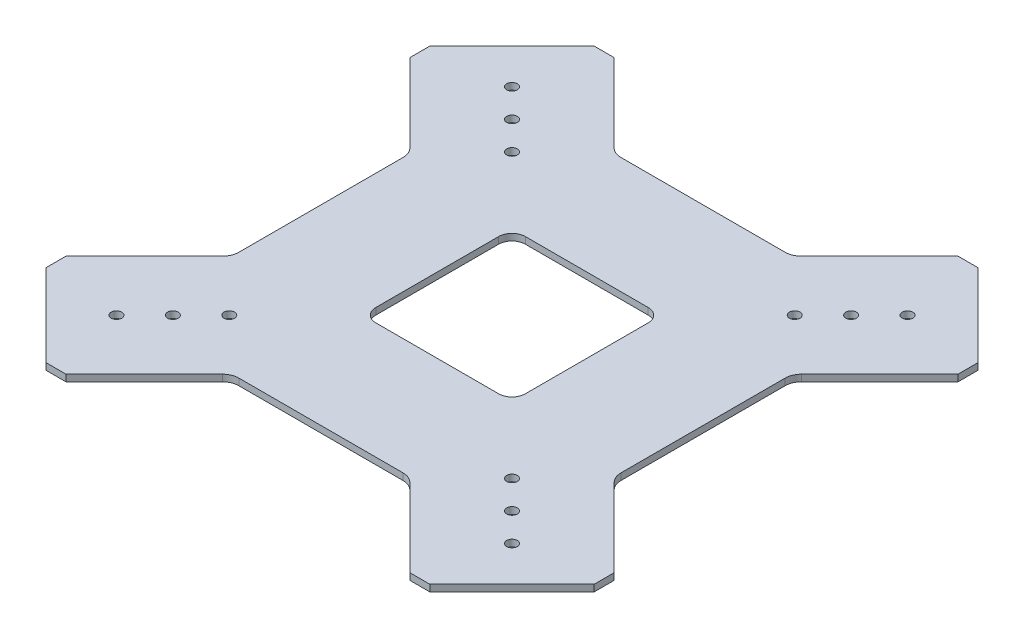
SolidWorks part; units mm, degrees
material "Thornel Mat VMA"
ref_plane "Front Plane" through (0, 0, 0) normal (0, 0, 1) x (1, 0, 0)
ref_plane "Top Plane" through (0, 0, 0) normal (0, 1, 0) x (1, 0, 0)
ref_plane "Right Plane" through (0, 0, 0) normal (1, 0, 0) x (0, 0, -1)
sketch "Sketch1" plane through (0, 0, 0) normal (0, 1, 0) x (1, 0, 0)
  line L0 (-57.7513, 82.5) -> (-82.5, 57.7513)
  line L1 (-57.7513, 82.5) -> (57.7513, 82.5)
  line L2 (-82.5, 57.7513) -> (-82.5, -57.7513)
  line L3 (-57.7513, -82.5) -> (57.7513, -82.5)
  line L4 (82.5, 57.7513) -> (82.5, -57.7513)
  line L5 (-70.1256, 70.1256) -> (70.1256, -70.1256) construction
  line L6 (-70.1256, -70.1256) -> (70.1256, 70.1256) construction
  line L7 (82.5, -57.7513) -> (57.7513, -82.5)
  line L8 (57.7513, 82.5) -> (82.5, 57.7513)
  line L9 (-82.5, -57.7513) -> (-57.7513, -82.5)
  point P0 (0, 0)
  point P9 (-70.1256, 70.1256)
  point P12 (70.1256, -70.1256)
  point P16 (70.1256, 70.1256)
  point P18 (-70.1256, -70.1256)
  dimension "D1" = 165
  dimension "D2" = 35
  dimension "D3" = 35
  dimension "D4" = 35
  dimension "D5" = 35
  dimension "D6" = 165
extrude "Boss-Extrude1" add sketch "Sketch1" along normal blind 2
sketch "Sketch2" plane through (0, 2, 0) normal (0, 1, 0) x (1, 0, 0)
  line L0 (0, -22.5) -> (0, 22.5) construction
  line L5 (22.5, -22.5) -> (-22.5, -22.5)
  line L6 (22.5, -22.5) -> (22.5, 22.5)
  line L7 (22.5, 22.5) -> (-22.5, 22.5)
  line L8 (-22.5, -22.5) -> (-22.5, 22.5)
  line L9 (-22.5, 0) -> (22.5, 0) construction
  dimension "D1" = 45
  dimension "D2" = 45
extrude "Cut-Extrude1" cut sketch "Sketch2" against normal through all
fillet "Fillet1" radius 4 4 edges at (22.5, 1, -22.5) (-22.5, 1, -22.5) (-22.5, 1, 22.5) (22.5, 1, 22.5)
sketch "Sketch3" plane through (0, 2, 0) normal (0, 1, 0) x (1, 0, 0)
  line L0 (51.7513, -82.5) -> (26.7513, -57.5)
  line L1 (-57.7513, -82.5) -> (57.7513, -82.5) construction
  line L2 (26.7513, -57.5) -> (-26.7513, -57.5)
  line L3 (-26.7513, -57.5) -> (-51.7513, -82.5)
  line L4 (0, -82.5) -> (0, -57.5) construction
  line L5 (51.7513, -82.5) -> (-51.7513, -82.5)
  line L6 (51.7513, 82.5) -> (26.7513, 57.5)
  line L7 (57.7513, 82.5) -> (-57.7513, 82.5) construction
  line L8 (26.7513, 57.5) -> (-26.7513, 57.5)
  line L9 (-26.7513, 57.5) -> (-51.7513, 82.5)
  line L10 (-51.7513, 82.5) -> (51.7513, 82.5)
  line L11 (0, 82.5) -> (0, 57.5) construction
  line L12 (82.5, -51.7513) -> (82.5, 51.7513)
  line L13 (82.5, -57.7513) -> (82.5, 57.7513) construction
  line L14 (82.5, 51.7513) -> (57.5, 26.7513)
  line L15 (57.5, 26.7513) -> (57.5, -26.7513)
  line L16 (57.5, -26.7513) -> (82.5, -51.7513)
  line L17 (82.5, 0) -> (57.5, 0) construction
  line L19 (-82.5, 57.7513) -> (-82.5, -57.7513) construction
  line L22 (-82.5, 51.7513) -> (-82.5, -51.7513)
  line L23 (-82.5, 0) -> (-57.5, 0) construction
  line L25 (-57.5, -26.7513) -> (-57.5, 26.7513)
  line L26 (-57.5, -26.7513) -> (-82.5, -51.7513)
  line L27 (-57.5, 26.7513) -> (-82.5, 51.7513)
  point P36 (-57.5, 0)
  line M15 (57.7513, 82.5) -> (-57.7513, 82.5)
  line M17 (-82.5, 57.7513) -> (-82.5, -57.7513)
  line M19 (-57.7513, -82.5) -> (57.7513, -82.5)
  line M21 (82.5, -57.7513) -> (82.5, 57.7513)
  dimension "D1" = 6
  dimension "D2" = 6
  dimension "D3" = 45
  dimension "D4" = 25
  dimension "D5" = 25
  dimension "D6" = 6
  dimension "D7" = 6
  dimension "D8" = 45
  dimension "D9" = 25
  dimension "D10" = 25
  dimension "D11" = 45
extrude "Cut-Extrude2" cut sketch "Sketch3" against normal through all contours L15 L16 L14 M21 | L2 L3 L0 M19 | L25 L27 L26 M17 | L9 L8 L6 M15
fillet "Fillet2" radius 5 8 edges at (26.7513, 1, -57.5) (-26.7513, 1, -57.5) (-57.5, 1, -26.7513) (-57.5, 1, 26.7513) (-26.7513, 1, 57.5) (26.7513, 1, 57.5) (57.5, 1, -26.7513) (57.5, 1, 26.7513)
hole_wizard "M3 Clearance Hole1" positions "Sketch6" profile "Sketch7" hole size "M3" standard "ANSI Metric" end condition through all
sketch "Sketch6" plane through (0, 0, 0) normal (0, -1, 0) x (-1, 0, 0)
  line L0 (70.1256, -70.1256) -> (-70.1256, 70.1256) construction
  line L1 (82.5, -57.7513) -> (57.7513, -82.5) construction
  line L2 (-82.5, 57.7513) -> (-57.7513, 82.5) construction
  line L4 (-70.1256, -70.1256) -> (70.1256, 70.1256) construction
  line L5 (-57.7513, -82.5) -> (-82.5, -57.7513) construction
  line L6 (57.7513, 82.5) -> (82.5, 57.7513) construction
  point P17 (59.519, -59.519)
  point P19 (51.0337, -51.0337)
  point P21 (42.5485, -42.5485)
  point P23 (-59.519, -59.519)
  point P25 (-51.0337, -51.0337)
  point P27 (-42.5485, -42.5485)
  point P29 (59.519, 59.519)
  point P31 (51.0337, 51.0337)
  point P33 (42.5485, 42.5485)
  point P35 (-42.5485, 42.5485)
  point P37 (-51.0337, 51.0337)
  point P39 (-59.519, 59.519)
  point P42 (0, 0)
  dimension "D1" = 12
  dimension "D2" = 12
  dimension "D3" = 15
  dimension "D4" = 12
  dimension "D5" = 12
  dimension "D6" = 15
  dimension "D7" = 12
  dimension "D8" = 12
  dimension "D9" = 15
  dimension "D10" = 12
  dimension "D11" = 12
  dimension "D12" = 15
sketch "Sketch7" plane through (59.519, 0, -59.519) normal (1, 0, 0) x (0, 0, -1)
  line L0 (0, 0) -> (0, 2)
  line L1 (0, 2) -> (1.6, 2)
  line L2 (1.6, 2) -> (1.6, 0)
  line L5 (1.6, 0) -> (0, 0)
  line L11 (0, -6.35) -> (0, 107.95) construction
  dimension "Thru Hole Dia." = 3.2
  dimension "Thru Hole Depth" = 2
